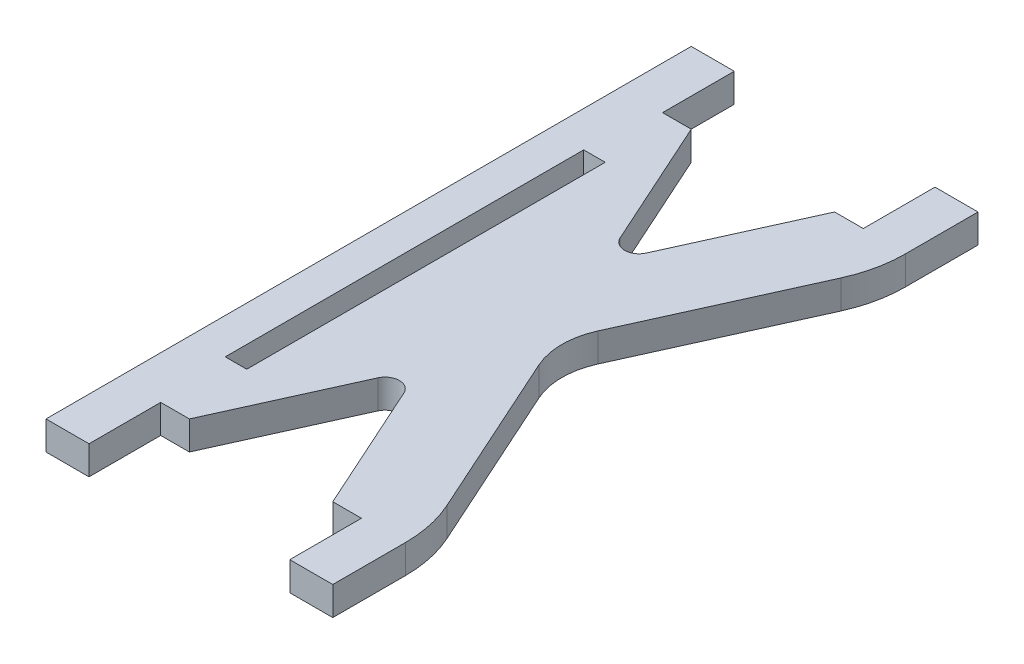
SolidWorks part; units mm, degrees
ref_plane "Front Plane" through (0, 0, 0) normal (0, 0, 1) x (1, 0, 0)
ref_plane "Top Plane" through (0, 0, 0) normal (0, 1, 0) x (1, 0, 0)
ref_plane "Right Plane" through (0, 0, 0) normal (1, 0, 0) x (0, 0, -1)
sketch "Sketch1" plane through (0, 0, 0) normal (0, 1, 0) x (1, 0, 0)
  line L0 (10, 0) -> (10, 35) construction
  line L1 (3, 0) -> (5, 0)
  line L2 (0, 0) -> (0, 2)
  line L3 (3, 35) -> (5, 35)
  line L4 (20, 0) -> (20, 2)
  line L6 (0, 35) -> (0, 40)
  line L7 (0, 40) -> (3, 40)
  line L8 (3, 35) -> (3, 40)
  line L9 (0, 17.5) -> (20, 17.5) construction
  line L10 (0, -5) -> (3, -5)
  line L11 (3, 0) -> (3, -5)
  line L12 (0, 0) -> (0, -5)
  line L13 (17, 35) -> (17, 40)
  line L14 (20, 40) -> (17, 40)
  line L15 (20, 35) -> (20, 40)
  line L16 (20, 0) -> (20, -5)
  line L17 (17, 0) -> (17, -5)
  line L18 (20, -5) -> (17, -5)
  line L19 (0, 33) -> (7, 17.5)
  line L20 (0, 2) -> (7, 17.5)
  line L21 (20, 33) -> (13, 17.5)
  line L22 (20, 2) -> (13, 17.5)
  line L23 (5, 35) -> (10, 23.9286)
  line L24 (15, 35) -> (10, 23.9286)
  line L25 (15, 0) -> (10, 11.0714)
  line L26 (5, 0) -> (10, 11.0714)
  line L27 (0, 33) -> (0, 35)
  line L28 (20, 33) -> (20, 35)
  line L29 (15, 35) -> (17, 35)
  line L30 (15, 0) -> (17, 0)
  point P33 (0, 0)
  dimension "D1" = 20
  dimension "D2" = 35
  dimension "D3" = 3
  dimension "D4" = 5
  dimension "D5" = 2
  dimension "D6" = 3
  dimension "D7" = 2
extrude "Boss-Extrude1" add sketch "Sketch1" along normal blind 2
fillet "Fillet1" radius 1 2 edges at (10, 1, -11.0714) (10, 1, -23.9286)
fillet "Fillet2" radius 5 2 edges at (7, 1, -17.5) (13, 1, -17.5)
fillet "Fillet3" radius 9 4 edges at (20, 1, -33) (0, 1, -33) (0, 1, -2) (20, 1, -2)
sketch "Sketch2" plane through (0, 2, 0) normal (0, 1, 0) x (1, 0, 0)
  line L0 (3, 35) -> (3, 0) construction
  line L1 (3, 0) -> (0, 0) construction
  line L2 (0, 0) -> (0, 34.938) construction
  line L3 (0, 34.938) -> (3, 35) construction
  line L4 (0, 17.5) -> (18.1383, 17.5) construction
  line L5 (3, 35) -> (0, 35)
  line L7 (3, 0) -> (0, 0)
  line L8 (0, 35) -> (0, 0)
  line L9 (3, 35) -> (9.0692, 17.5)
  line L10 (9.0692, 17.5) -> (3, 0)
extrude "Boss-Extrude2" add sketch "Sketch2" against normal blind 2
sketch "Sketch3" plane through (0, 2, 0) normal (0, 1, 0) x (1, 0, 0)
  line L0 (0, 17.5) -> (13.4862, 17.5) construction
  line L1 (0, 40) -> (0, -5) construction
  line L3 (2.5, 5) -> (4, 5)
  line L4 (2.5, 5) -> (2.5, 30)
  line L5 (2.5, 30) -> (4, 30)
  line L6 (4, 5) -> (4, 30)
  line L7 (2.5, 5) -> (4, 30) construction
  line L8 (2.5, 30) -> (4, 5) construction
  arc A0 (13.9294, 19.5579) -> (13.9294, 15.4421) centre (18.4862, 17.5) ccw construction
  point P7 (3.25, 17.5)
  dimension "D1" = 25
  dimension "D2" = 1.5
  dimension "D3" = 2.5
extrude "Cut-Extrude1" cut sketch "Sketch3" against normal blind 2
